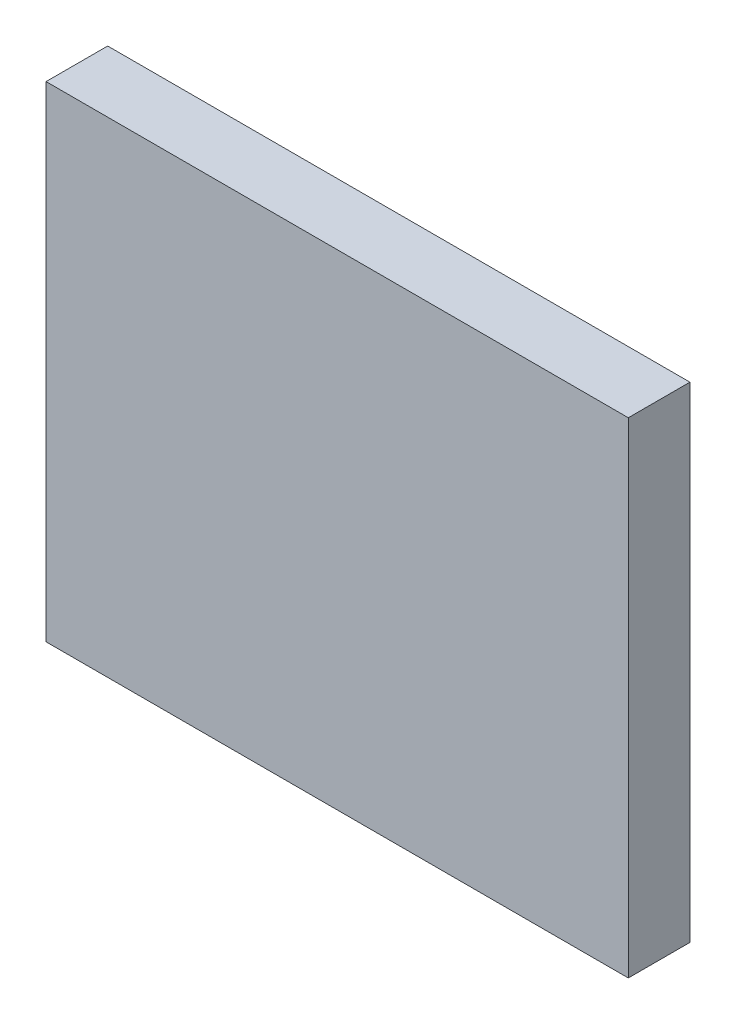
SolidWorks part; units mm, degrees
ref_plane "Front Plane" through (0, 0, 0) normal (0, 0, 1) x (1, 0, 0)
ref_plane "Top Plane" through (0, 0, 0) normal (0, 1, 0) x (1, 0, 0)
ref_plane "Right Plane" through (0, 0, 0) normal (1, 0, 0) x (0, 0, -1)
sketch "Sketch1" plane through (0, 0, 0) normal (0, 0, 1) x (1, 0, 0)
  line L1 (120, -100) -> (-120, -100)
  line L2 (120, -100) -> (120, 100)
  line L3 (120, 100) -> (-120, 100)
  line L4 (-120, -100) -> (-120, 100)
  line L5 (120, -100) -> (-120, 100) construction
  line L6 (120, 100) -> (-120, -100) construction
  point P0 (0, 0)
  dimension "D1" = 240
  dimension "D2" = 200
extrude "Boss-Extrude1" add sketch "Sketch1" along normal blind 25.4
